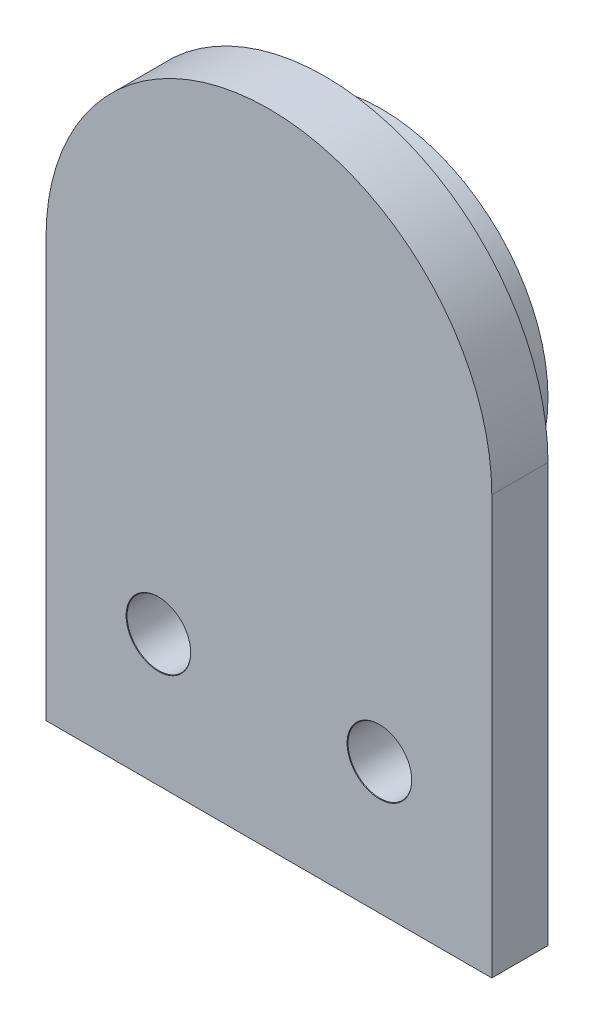
SolidWorks part; units mm, degrees
ref_plane "Front Plane" through (0, 0, 0) normal (0, 0, 1) x (1, 0, 0)
ref_plane "Top Plane" through (0, 0, 0) normal (0, 1, 0) x (1, 0, 0)
ref_plane "Right Plane" through (0, 0, 0) normal (1, 0, 0) x (0, 0, -1)
sketch "Sketch1" plane through (0, 0, 0) normal (0, 0, 1) x (1, 0, 0)
  line L0 (-11.9, 0) -> (-11.9, -22.34)
  line L1 (-11.9, -22.34) -> (11.9, -22.34)
  line L2 (11.9, -22.34) -> (11.9, 0)
  arc A0 (11.9, 0) -> (-11.9, 0) centre (0, 0) ccw
  dimension "D1" = 22.34
  dimension "D2" = 23.8
extrude "Boss-Extrude1" add sketch "Sketch1" along normal blind 3
sketch "Sketch2" plane through (0, 0, 0) normal (0, 0, -1) x (-1, 0, 0)
  circle A0 centre (0, 0) radius 8.9
  dimension "D1" = 17.8
extrude "Boss-Extrude2" add sketch "Sketch2" along normal blind 3
sketch "Sketch3" plane through (0, 0, -3) normal (0, 0, -1) x (-1, 0, 0)
  circle A0 centre (0, 0) radius 2
  dimension "D1" = 4
extrude "Boss-Extrude3" add sketch "Sketch3" along normal blind 3
hole_wizard "M3 Clearance Hole1" positions "3DSketch1" profile "Sketch5" hole size "M3" standard "ANSI Metric" end condition through all
sketch3d "3DSketch1"
  line L0 (-11.9, -22.34, 3) -> (11.9, -22.34, 3) construction
  line L1 (-11.9, 0, 3) -> (-11.9, -22.34, 3) construction
  line L2 (11.9, -22.34, 3) -> (11.9, 0, 3) construction
  point P0 (-5.9, -15.34, 3)
  point P2 (5.9, -15.34, 3)
  point P5 (0, 0, 0)
  dimension "D1" = 7
  dimension "D2" = 6
  dimension "D3" = 6
sketch "Sketch5" plane through (-5.9, -15.34, 3) normal (1, 0, 0) x (0, -1, 0)
  line L0 (0, 0) -> (0, 9)
  line L1 (0, 9) -> (1.7, 9)
  line L2 (1.7, 9) -> (1.7, 0.025)
  line L3 (1.7, 0.025) -> (1.725, 0)
  line L5 (1.725, 0) -> (0, 0)
  line L6 (-1.7, 0.025) -> (-1.725, 0) construction
  line L11 (0, -6.35) -> (0, 107.95) construction
  dimension "Thru Hole Dia." = 3.4
  dimension "Thru Hole Depth" = 9
  dimension "Near C'Sink Dia." = 3.45
  dimension "Near C'Sink Angle" = 90
